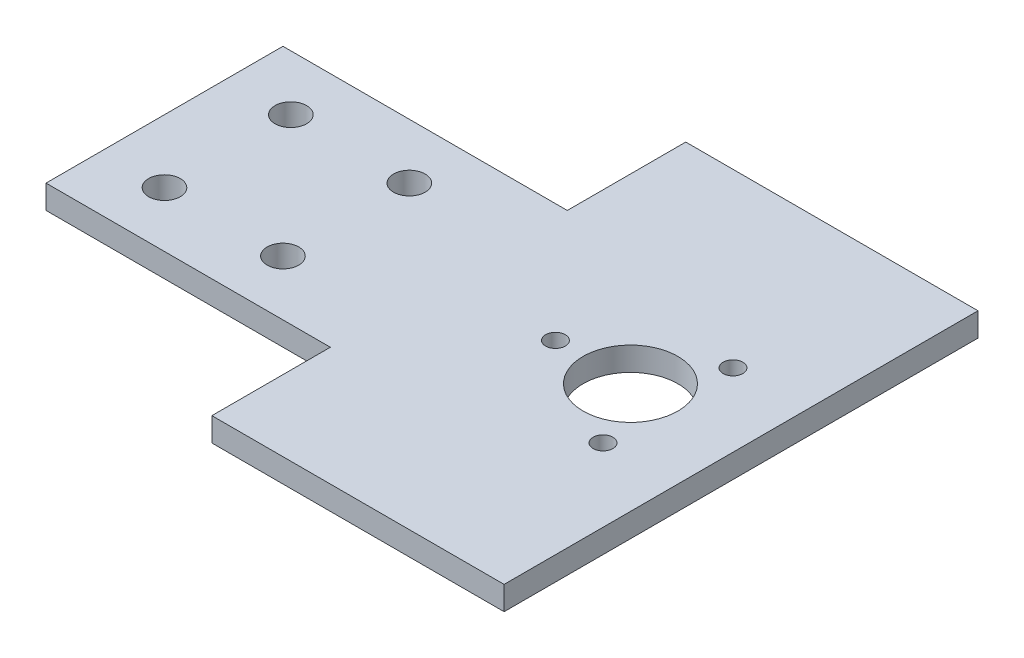
SolidWorks part; units mm, degrees
ref_plane "前视基准面" through (0, 0, 0) normal (0, 0, 1) x (1, 0, 0)
ref_plane "上视基准面" through (0, 0, 0) normal (0, 1, 0) x (1, 0, 0)
ref_plane "右视基准面" through (0, 0, 0) normal (1, 0, 0) x (0, 0, -1)
other "Configuration Table"
sketch "草图1" plane through (0, 0, 0) normal (0, 1, 0) x (1, 0, 0)
  line L0 (0, 0) -> (0, 30)
  line L1 (0, 30) -> (36, 30)
  line L2 (36, 30) -> (36, 45)
  line L3 (36, 45) -> (73, 45)
  line L4 (73, 45) -> (73, -15)
  line L5 (73, -15) -> (36, -15)
  line L6 (36, -15) -> (36, 0)
  line L7 (36, 0) -> (0, 0)
  dimension "D1" = 30
  dimension "D2" = 36
  dimension "D3" = 37
  dimension "D4" = 60
extrude "凸台-拉伸1" add sketch "草图1" along normal blind 3
sketch "草图2" plane through (0, 3, 0) normal (0, 1, 0) x (1, 0, 0)
  line L0 (36, 30) -> (0, 30) construction
  line L1 (8, 23) -> (23, 23) construction
  line L2 (8, 23) -> (8, 7) construction
  line L3 (8, 7) -> (23, 7) construction
  line L4 (23, 23) -> (23, 7) construction
  line L5 (0, 30) -> (0, 0) construction
  line L6 (73, -15) -> (73, 45) construction
  line L7 (73, 15) -> (0, 15) construction
  circle A0 centre (8, 23) radius 2
  circle A1 centre (23, 23) radius 2
  circle A2 centre (8, 7) radius 2
  circle A3 centre (23, 7) radius 2
  circle A4 centre (59, 15) radius 6
  dimension "D5" = 4
  dimension "D6" = 12
  dimension "D1" = 16
  dimension "D2" = 7
  dimension "D3" = 8
  dimension "D4" = 15
  dimension "D7" = 14
extrude "切除-拉伸1" cut sketch "草图2" against normal blind 3
sketch "草图3" plane through (0, 3, 0) normal (0, 1, 0) x (1, 0, 0)
  line L0 (59, 15) -> (49.5, 15) construction
  line L1 (59, 15) -> (63.75, 23.2272) construction
  line L2 (59, 15) -> (63.75, 6.7728) construction
  circle A0 centre (59, 15) radius 6 construction
  circle A1 centre (59, 15) radius 6 construction
  circle A2 centre (59, 15) radius 9.5 construction
  circle A3 centre (63.75, 23.2272) radius 1.25
  circle A4 centre (63.75, 6.7728) radius 1.25
  circle A5 centre (49.5, 15) radius 1.25
  dimension "D1" = 19
  dimension "D4" = 2.5
  dimension "D2" = 120
  dimension "D3" = 120
extrude "切除-拉伸2" cut sketch "草图3" against normal blind 3
